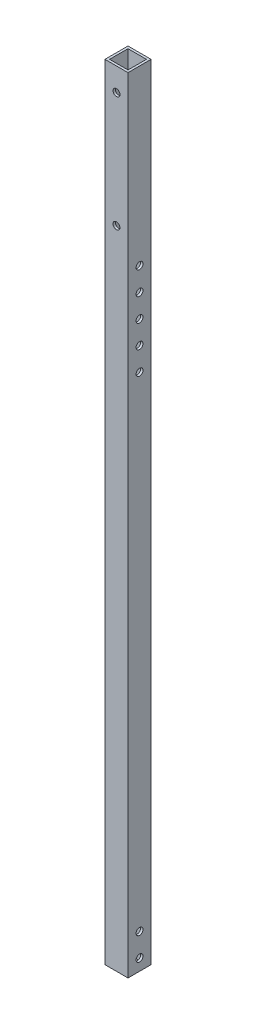
SolidWorks part; units mm, degrees
material "氧化铝"
ref_plane "前视基准面" through (0, 0, 0) normal (0, 0, 1) x (1, 0, 0)
ref_plane "上视基准面" through (0, 0, 0) normal (0, 1, 0) x (1, 0, 0)
ref_plane "右视基准面" through (0, 0, 0) normal (1, 0, 0) x (0, 0, -1)
other "Configuration Table"
sketch "草图1" plane through (0, 0, 0) normal (0, 1, 0) x (1, 0, 0)
  line L1 (-4, -4) -> (4, -4)
  line L2 (-4, -4) -> (-4, 4)
  line L3 (-4, 4) -> (4, 4)
  line L4 (4, -4) -> (4, 4)
  line L5 (-4, -4) -> (4, 4) construction
  line L6 (-4, 4) -> (4, -4) construction
  line L7 (-5, 5) -> (5, 5)
  line L8 (-5, 5) -> (-5, -5)
  line L9 (-5, -5) -> (5, -5)
  line L10 (5, 5) -> (5, -5)
  line L11 (-5, 5) -> (5, -5) construction
  line L12 (-5, -5) -> (5, 5) construction
  point P0 (0, 0)
  point P6 (0, 0)
  dimension "D1" = 1
  dimension "D2" = 10
  dimension "D3" = 10
  dimension "D4" = 1
extrude "凸台-拉伸1" add sketch "草图1" along normal blind 340
sketch "草图2" plane through (-5, 0, 0) normal (-1, 0, 0) x (0, 0, 1)
  line L0 (0, 0) -> (0, 340) construction
  line L1 (-5, 340) -> (5, 340) construction
  line L2 (-5, 0) -> (5, 0) construction
  circle A0 centre (0, 5) radius 1.5
  circle A1 centre (0, 15) radius 1.5
  circle A2 centre (0, 225) radius 1.5
  circle A7 centre (0, 235) radius 1.5
  circle A8 centre (0, 245) radius 1.5
  circle A9 centre (0, 255) radius 1.5
  circle A10 centre (0, 265) radius 1.5
  point P13 (0, 144.4264)
  point P14 (0, 0)
  point P23 (0, 245)
  point P25 (0, 265.4511)
  dimension "D3" = 3
  dimension "D1" = 10
  dimension "D2" = 5
  dimension "D5" = 95
  dimension "D6" = 10
  dimension "D4" = 5
extrude "切除-拉伸1" cut sketch "草图2" against normal blind 30
sketch "草图3" plane through (0, 0, -5) normal (0, 0, -1) x (-1, 0, 0)
  line L0 (0, 0) -> (0, 340) construction
  line L1 (-5, 340) -> (5, 340) construction
  circle A0 centre (0, 280) radius 1.5
  circle A1 centre (0, 330) radius 1.5
  point P11 (-5, 332.4932)
  dimension "D3" = 3
  dimension "D1" = 50
  dimension "D2" = 10
extrude "切除-拉伸2" cut sketch "草图3" against normal blind 10
